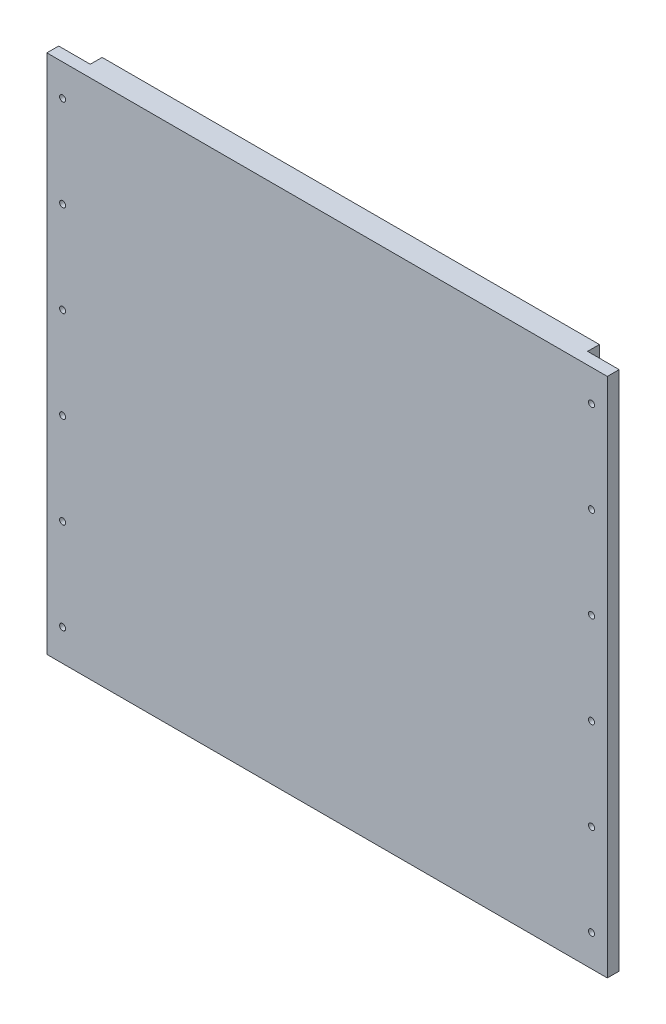
SolidWorks part; units mm, degrees
ref_plane "Front Plane" through (0, 0, 0) normal (0, 0, 1) x (1, 0, 0)
ref_plane "Top Plane" through (0, 0, 0) normal (0, 1, 0) x (1, 0, 0)
ref_plane "Right Plane" through (0, 0, 0) normal (1, 0, 0) x (0, 0, -1)
sketch "Sketch1" plane through (0, 0, 0) normal (0, 1, 0) x (1, 0, 0)
  line L1 (-17.1702, 1.0203) -> (382.8798, 1.0203)
  line L2 (-17.1702, 1.0203) -> (-17.1702, -8.5047)
  line L3 (-17.1702, -18.0297) -> (382.8798, -18.0297)
  line L4 (382.8798, 1.0203) -> (382.8798, -8.5047)
  line L5 (382.8798, -8.5047) -> (408.2798, -8.5047)
  line L7 (382.8798, -18.0297) -> (408.2798, -18.0297)
  line L8 (408.2798, -8.5047) -> (408.2798, -18.0297)
  line L9 (-17.1702, -8.5047) -> (-42.5702, -8.5047)
  line L11 (-17.1702, -18.0297) -> (-42.5702, -18.0297)
  line L12 (-42.5702, -8.5047) -> (-42.5702, -18.0297)
  dimension "D1" = 400.05
  dimension "D2" = 25.4
  dimension "D3" = 25.4
  dimension "D4" = 9.525
  dimension "D5" = 19.05
  dimension "D6" = 9.525
extrude "Boss-Extrude1" add sketch "Sketch1" along normal blind 419.1
hole_wizard "#8 Clearance Hole1" positions "Sketch3" profile "Sketch2" hole size "#8" standard "ANSI Inch"
sketch "Sketch3" plane through (0, 0, 18.0297) normal (0, 0, 1) x (1, 0, 0)
  line L0 (-42.5702, 0) -> (408.2798, 0) construction
  line L1 (-42.5702, 419.1) -> (-42.5702, 0) construction
  line L2 (408.2798, 419.1) -> (408.2798, 0) construction
  point P0 (-29.8702, 393.7)
  point P2 (-29.8702, 320.04)
  point P4 (-29.8702, 246.38)
  point P6 (-29.8702, 172.72)
  point P8 (-29.8702, 99.06)
  point P10 (-29.8702, 25.4)
  point P12 (395.5798, 25.4)
  point P14 (395.5798, 99.06)
  point P16 (395.5798, 172.72)
  point P18 (395.5798, 246.38)
  point P20 (395.5798, 320.04)
  point P22 (395.5798, 393.7)
other "AlignGroup1" parameters "D1"=0, "D2"=25.4, "D3"=99.06, "D4"=172.72, "D5"=246.38, "D6"=320.04, "D7"=393.7, "D8"=16.3032, "D9"=11.7869
sketch "Sketch2" plane through (-29.8702, 393.7, 18.0297) normal (1, 0, 0) x (0, -1, 0)
  line L0 (0, 0) -> (0, 11.1286)
  line L1 (0, 11.1286) -> (2.4574, 9.652)
  line L2 (2.4574, 9.652) -> (2.4574, 0)
  line L5 (2.4574, 0) -> (0, 0)
  line L10 (0, 11.1286) -> (-2.4574, 9.652) construction
  line L11 (0, -6.35) -> (0, 107.95) construction
  dimension "Hole Dia." = 4.9149
  dimension "Hole Depth" = 9.652
  dimension "Drill Angle" = 118
